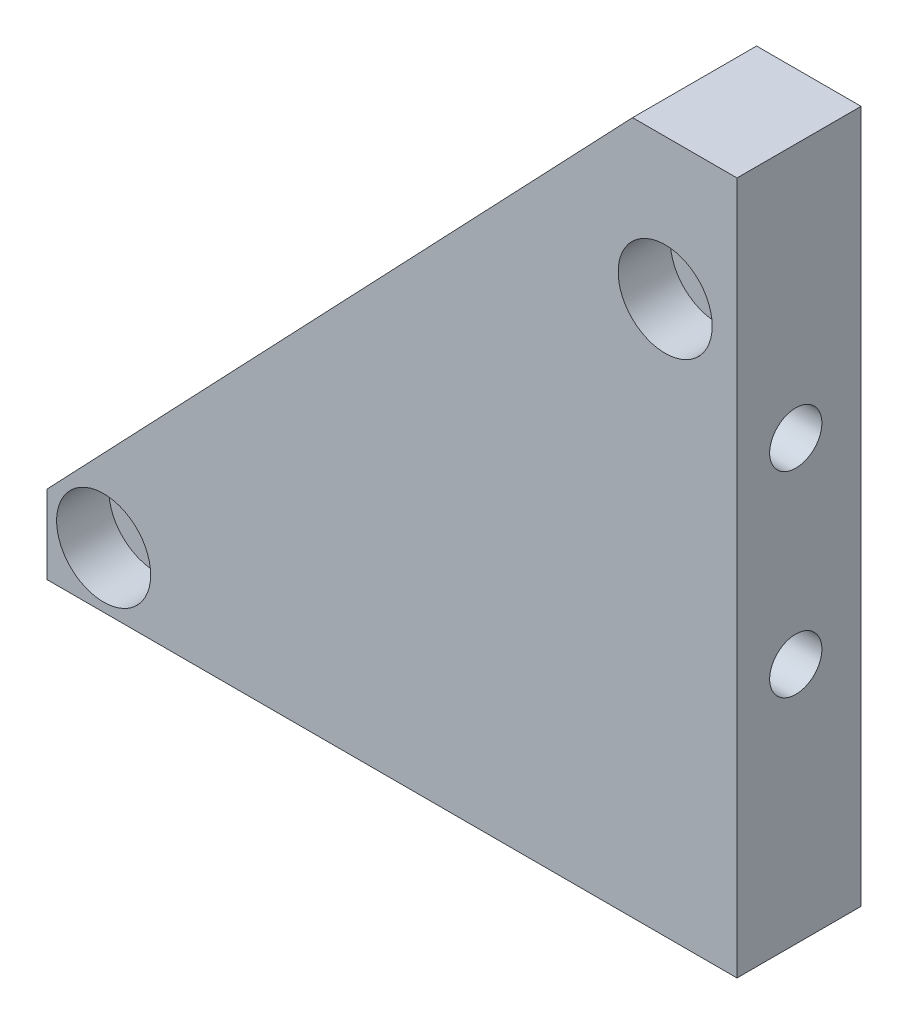
SolidWorks part; units mm, degrees
ref_plane "Front Plane" through (0, 0, 0) normal (0, 0, 1) x (1, 0, 0)
ref_plane "Top Plane" through (0, 0, 0) normal (0, 1, 0) x (1, 0, 0)
ref_plane "Right Plane" through (0, 0, 0) normal (1, 0, 0) x (0, 0, -1)
sketch "Sketch1" plane through (0, 0, 0) normal (0, 0, 1) x (1, 0, 0)
  line L5 (-4.1227, -0.1048) -> (-12.1227, -0.1048)
  line L8 (-10.1227, -53.1604) -> (-4.1227, -53.1604)
  line L9 (-4.1227, -53.1604) -> (-4.1227, -0.1048)
  line L10 (-12.1227, -0.1048) -> (-56.9644, -47.1604)
  line L11 (-56.9644, -47.1604) -> (-56.9644, -53.1604)
  line L12 (-56.9644, -53.1604) -> (-10.1227, -53.1604)
  line L13 (-56.9644, -50.1604) -> (-4.1227, -50.1604) construction
  circle A0 centre (-52.6227, -48.8846) radius 2
  circle A1 centre (-9.6227, -10.8846) radius 2
  dimension "D8" = 4
  dimension "D11" = 4
  dimension "D12" = 4.3416
  dimension "D13" = 4.2758
  dimension "D1" = 65
  dimension "D2" = 4.1227
  dimension "D3" = 53.0556
  dimension "D4" = 0.1048
  dimension "D5" = 6
  dimension "D6" = 6
  dimension "D7" = 8
  dimension "D9" = 5.5
  dimension "D10" = 10.7798
extrude "Boss-Extrude1" add sketch "Sketch1" along normal blind 9.5
sketch "Sketch2" plane through (-4.1227, 0, 0) normal (1, 0, 0) x (0, 0, -1)
  line L0 (0, -53.1604) -> (0, -0.1048) construction
  line L1 (-9.5, -53.1604) -> (0, -53.1604) construction
  circle A0 centre (-5, -19.601) radius 2
  circle A1 centre (-5, -34.601) radius 2
  dimension "D1" = 5
  dimension "D2" = 15
  dimension "D4" = 18.5594
  dimension "D5" = 4
  dimension "D3" = 5
extrude "Cut-Extrude1" cut sketch "Sketch2" against normal blind 12
sketch "Sketch3" plane through (0, 0, 9.5) normal (0, 0, 1) x (1, 0, 0)
  line L0 (-56.9644, -47.1604) -> (-56.9644, -53.1604) construction
  line L1 (-56.9644, -53.1604) -> (-4.1227, -53.1604) construction
  circle A0 centre (-52.6227, -48.8846) radius 3.6
  dimension "D1" = 7.2
  dimension "D2" = 4.3416
  dimension "D3" = 4.2758
extrude "Cut-Extrude2" cut sketch "Sketch3" against normal blind 4
sketch "Sketch4" plane through (0, 0, 9.5) normal (0, 0, 1) x (1, 0, 0)
  line L0 (-4.1227, -0.1048) -> (-12.1227, -0.1048) construction
  line L1 (-4.1227, -53.1604) -> (-4.1227, -0.1048) construction
  circle A0 centre (-9.6227, -10.8846) radius 3.6
  dimension "D1" = 7.2
  dimension "D2" = 10.7798
  dimension "D3" = 5.5
extrude "Cut-Extrude3" cut sketch "Sketch4" against normal blind 4
